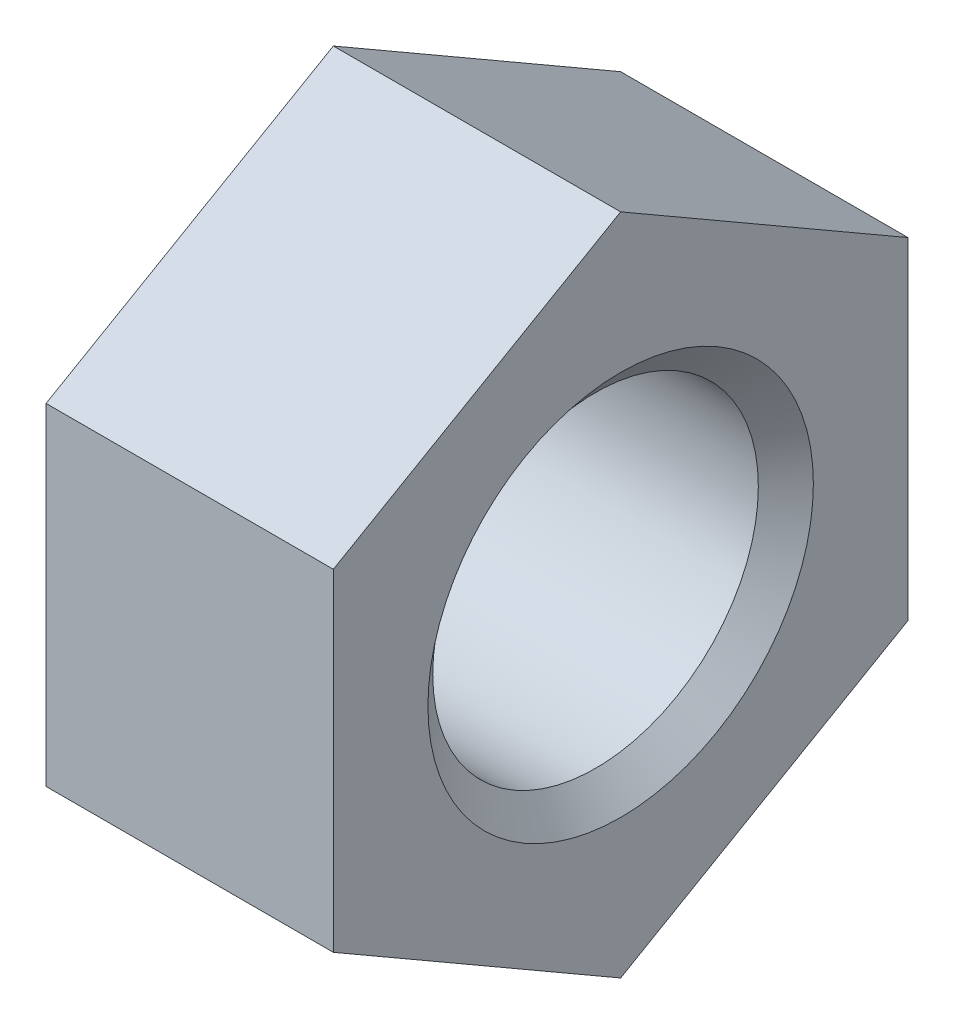
SolidWorks part; units mm, degrees
ref_plane "前视基准面" through (0, 0, 0) normal (0, 0, 1) x (1, 0, 0)
ref_plane "上视基准面" through (0, 0, 0) normal (0, 1, 0) x (1, 0, 0)
ref_plane "右视基准面" through (0, 0, 0) normal (1, 0, 0) x (0, 0, -1)
other "Configuration Table"
sketch "草图2" plane through (0, 0, 0) normal (1, 0, 0) x (0, 0, -1)
  line L1 (6, -3.4641) -> (6, 3.4641)
  line L2 (6, 3.4641) -> (0, 6.9282)
  line L3 (0, 6.9282) -> (-6, 3.4641)
  line L4 (-6, 3.4641) -> (-6, -3.4641)
  line L5 (-6, -3.4641) -> (0, -6.9282)
  line L6 (0, -6.9282) -> (6, -3.4641)
  circle A0 centre (0, 0) radius 6 construction
extrude "凸台-拉伸1" add sketch "草图2" along normal blind 6
sketch "草图3" plane through (6, 0, 0) normal (1, 0, 0) x (0, 0, -1)
  circle A0 centre (0, 0) radius 1.0038
hole_wizard "M8 螺纹孔1" positions "3D草图1" profile "草图4" tap size "M8" standard "GB" end condition through all
sketch3d "3D草图1"
  point P1 (0, 0, 0)
  point P4 (0, 0, 0)
  point P6 (0, 0, 0)
  point P8 (6, 0, 0)
sketch "草图4" plane through (6, 0, 0) normal (0, 1, 0) x (0, 0, -1)
  line L0 (0, 0) -> (0, 6)
  line L1 (0, 6) -> (3.4, 6)
  line L2 (3.4, 6) -> (3.4, 0.5244)
  line L3 (3.4, 0.5244) -> (4.025, 0)
  line L5 (4.025, 0) -> (0, 0)
  line L6 (-3.4, 0.5244) -> (-4.025, 0) construction
  line L11 (0, -6.35) -> (0, 107.95) construction
  dimension "通孔螺纹孔钻头直径" = 6.8
  dimension "通孔螺纹孔钻头深度" = 6
  dimension "近端锥形沉头孔直径" = 8.05
  dimension "近端锥形沉头孔角度" = 100
cosmetic thread "孔螺蚊线1" parameters "D2"=8
cosmetic thread "孔螺蚊线2" parameters "D2"=8
cosmetic thread "孔螺蚊线3" parameters "D2"=8
cosmetic thread "孔螺蚊线4" parameters "D2"=8
